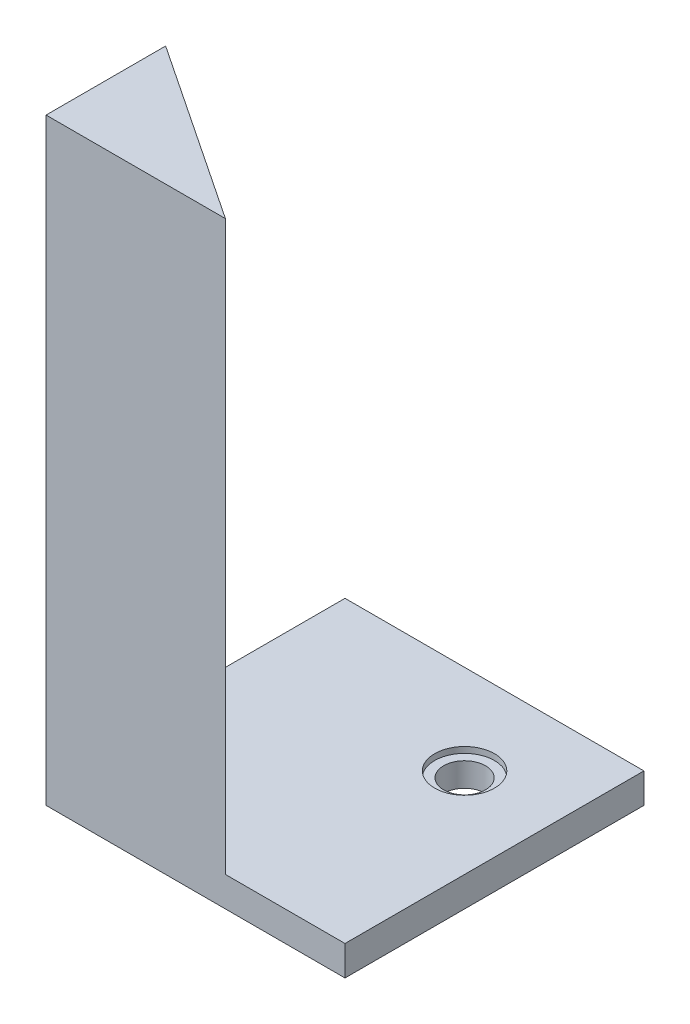
SolidWorks part; units mm, degrees
ref_plane "Front Plane" through (0, 0, 0) normal (0, 0, 1) x (1, 0, 0)
ref_plane "Top Plane" through (0, 0, 0) normal (0, 1, 0) x (1, 0, 0)
ref_plane "Right Plane" through (0, 0, 0) normal (1, 0, 0) x (0, 0, -1)
sketch "Sketch1" plane through (0, 0, 0) normal (0, 1, 0) x (1, 0, 0)
  line L0 (0, 0) -> (0, 20)
  line L1 (0, 0) -> (30, 0)
  line L2 (0, 20) -> (30, 0)
  dimension "D1" = 20
  dimension "D2" = 30
extrude "Boss-Extrude1" add sketch "Sketch1" along normal blind 100
sketch "Sketch2" plane through (0, 0, 0) normal (0, -1, 0) x (1, 0, 0)
  line L1 (0, 0) -> (50, 0)
  line L2 (0, 0) -> (0, -50)
  line L3 (0, -50) -> (50, -50)
  line L4 (50, 0) -> (50, -50)
  dimension "D1" = 50
  dimension "D2" = 50
extrude "Boss-Extrude2" add sketch "Sketch2" against normal blind 5
sketch "Sketch3" plane through (0, 5, 0) normal (0, 1, 0) x (1, 0, 0)
  line L0 (0, 50) -> (50, 50) construction
  line L1 (50, 50) -> (50, 0) construction
  circle A0 centre (35, 35) radius 3.5
  dimension "D1" = 7
  dimension "D3" = 15
  dimension "D2" = 15
extrude "Cut-Extrude1" cut sketch "Sketch3" against normal through all
sketch "Sketch4" plane through (0, 5, 0) normal (0, 1, 0) x (1, 0, 0)
  circle A0 centre (35, 35) radius 5
  dimension "D1" = 10
extrude "Cut-Extrude2" cut sketch "Sketch4" against normal blind 1
